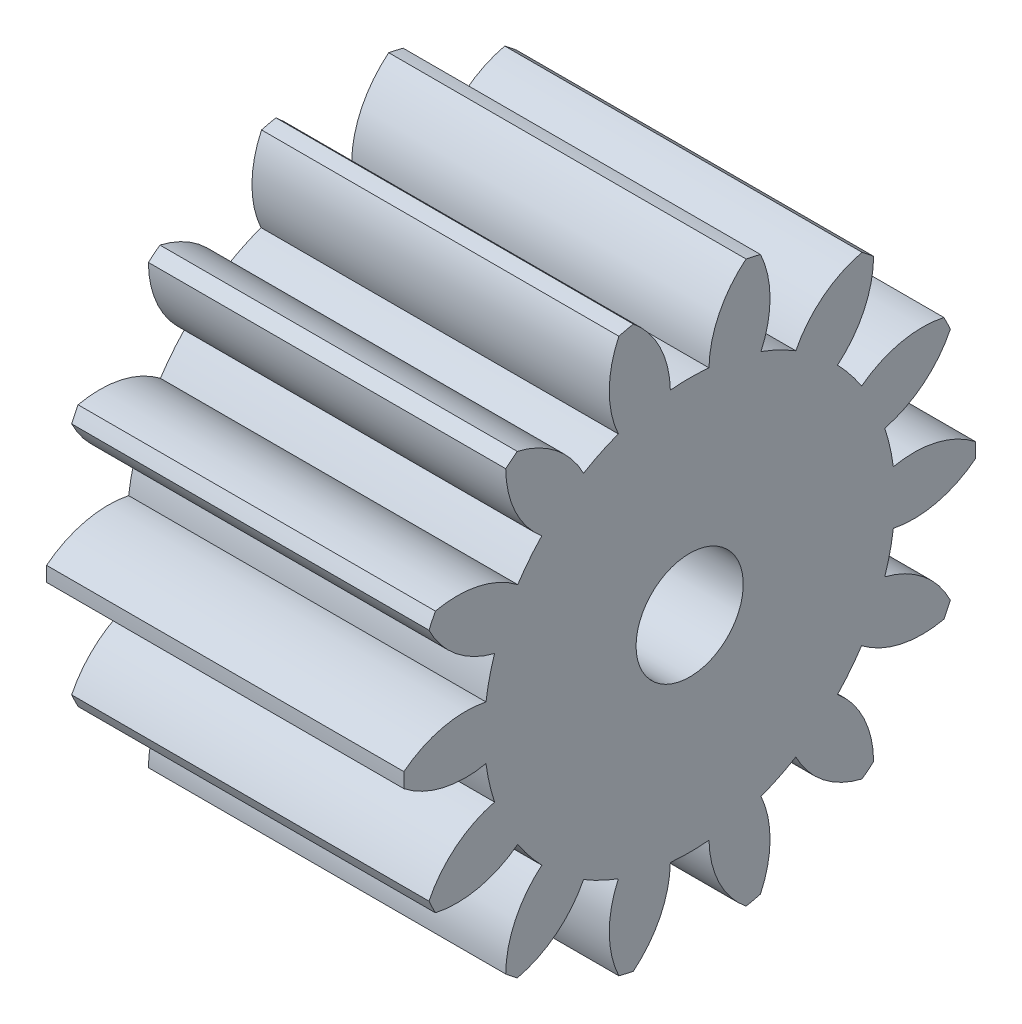
SolidWorks part; units mm, degrees
ref_plane "Plane1" through (0, 0, 0) normal (0, 0, 1) x (1, 0, 0)
ref_plane "Plane2" through (0, 0, 0) normal (0, 1, 0) x (1, 0, 0)
ref_plane "Plane3" through (0, 0, 0) normal (1, 0, 0) x (0, 0, -1)
other "Configuration Table"
sketch "HoldingSke" plane through (0, 0, 0) normal (0, 1, 0) x (1, 0, 0)
  line L0 (0, 0) -> (0.9703, -0.2419)
  line L1 (-15, 0) -> (100, 0) construction
  line L2 (0, 0) -> (-2.1039, 2.3779)
  line L3 (0, 0) -> (-11.863, 4.5341)
  line L4 (0, 0) -> (8.3795, 2.0892)
  line L5 (0, 0) -> (-46.8476, -17.4728)
  line L6 (0, 0) -> (-8.2896, -5.593)
  line L7 (-2.1039, 2.3779) -> (8.6586, 51.2059)
  line L8 (-76.2, 54.61) -> (-75.7, 54.61)
  line L9 (-71.009, 38.7566) -> (-53.1078, 45.2721)
  line L10 (-76.2, 71.12) -> (104.1128, 71.12)
  line L11 (0, 0) -> (-10, 0)
  line L12 (-76.2, 101.6) -> (-76.162, 101.6)
  line L13 (24.9733, 27.94) -> (52.9518, 28.4284)
  line L14 (24.9733, 27.94) -> (24.9743, 27.94)
  line L15 (24.9733, 27.94) -> (100.4006, 29.5858)
  line L16 (-63.627, -1) -> (-12.827, -1)
  circle A0 centre (0, 0) radius 1.5
  circle A1 centre (0, 0) radius 5.749
  circle A2 centre (0, 0) radius 37.5
  circle A3 centre (0, 0) radius 1.5
  dimension "MHD" = 11.498
  dimension "Hub_dia" = 75
  dimension "Bore" = 3
  dimension "MBD" = 3
  dimension "Num_teeth" = 14
  dimension "Pitch" = 1
  dimension "Overall_len" = 50
  dimension "Show_teeth" = 14
  dimension "Thickness" = 10
  dimension "OAL" = 50.0001
  dimension "T_dim" = 0.5
  dimension "Ap" = 20
  dimension "H" = 19.05
  dimension "Pitch_radius" = 180.3128
  dimension "Width" = 10
  dimension "Backlash" = 0.038
  dimension "Addendum_fac" = 1
  dimension "Dedendum_fac" = 1.25
  dimension "Clearance_fac" = 0.25
  dimension "Dedendum_add" = 0.001
  dimension "Module" = 1
sketch "BasProSke" plane through (0, 0, 0) normal (0, 1, 0) x (1, 0, 0)
  line L0 (-10, 0) -> (60, 0) construction
  line L1 (0, 0) -> (0, 8)
  line L2 (0, 0) -> (10, 0)
  line L3 (10, 0) -> (10, 8)
  line L4 (10, 8) -> (0, 8)
  dimension "Thickness" = 10
  dimension "Diameter" = 16
revolve "Base-Revolve" add sketch "BasProSke" angle 360 about L0
sketch "TooCutSke" plane through (0, 0, 0) normal (1, 0, 0) x (0, 0, -1)
  line L1 (0, 0) -> (0, 107) construction
  line L2 (0, 0) -> (-0.8502, 6.9482) construction
  line L3 (0, 0) -> (-3.0989, 13.5772) construction
  line L4 (-0.8502, 6.9482) -> (-1.5494, 6.7886) construction
  arc A0 (0.5404, 5.7235) -> (-0.5404, 5.7235) centre (0, 0) ccw
  arc A1 (1.6036, 7.8636) -> (-1.6036, 7.8636) centre (0, 0) ccw
  circle A2 centre (0, 0) radius 7 construction
  circle A3 centre (0, 0) radius 6.5778 construction
  arc A4 (-0.5404, 5.7235) -> (-1.6036, 7.8636) centre (-3.3398, 5.6669) ccw
  arc A5 (1.6036, 7.8636) -> (0.5404, 5.7235) centre (3.3398, 5.6669) ccw
  dimension "Root_dia" = 11.498
  dimension "Overcut_dia" = 16.0508
  dimension "Pitch_dia" = 14
  dimension "Base_dia" = 13.1557
  dimension "Flank_rad" = 2.8
  dimension "Half_ang" = 12.857
  dimension "Half_CT" = 0.7173
extrude "ToothCut" cut sketch "TooCutSke" along normal through all
fillet "Breaks" [suppressed] radius 0.02
fillet "RootFillets" [suppressed] radius 0.251
pattern_circular "TeethCuts" count 14 every 25.714 about axis through (-10, 0, 0) along (1, 0, 0) of "ToothCut", "RootFillets", "Breaks"
sketch "HubNeaOneSke" plane through (0, 0, 0) normal (-1, 0, 0) x (0, 0, 1)
  circle A0 centre (0, 0) radius 5.749
  dimension "Diameter" = 11.498
extrude "HubNearOne" [suppressed] add sketch "HubNeaOneSke" along normal blind 40.0001
sketch "HubNeaBotSke" plane through (0, 0, 0) normal (-1, 0, 0) x (0, 0, 1)
  circle A0 centre (0, 0) radius 5.749
  dimension "Diameter" = 11.498
extrude "HubNearBoth" [suppressed] add sketch "HubNeaBotSke" along normal blind 20
ref_plane "FarPln" through (10, 0, 0) normal (1, 0, 0) x (0, 0, -1)
sketch "HubFarSke" plane through (10, 0, 0) normal (1, 0, 0) x (0, 0, -1)
  circle A0 centre (0, 0) radius 5.749
  dimension "Diameter" = 11.498
extrude "HubFar" [suppressed] add sketch "HubFarSke" along normal blind 20
sketch "BorSke" plane through (0, 0, 0) normal (1, 0, 0) x (0, 0, -1)
  circle A0 centre (0, 0) radius 1.5
  dimension "Diameter" = 3
extrude "Bore" cut sketch "BorSke" along normal mid plane 100.0001
sketch "KeySke" plane through (0, 0, 0) normal (1, 0, 0) x (0, 0, -1)
  line L0 (-0.6, 0) -> (-0.6, 2)
  line L1 (-0.6, 2) -> (0.6, 2)
  line L2 (0.6, 2) -> (0.6, 0)
  line L3 (0, 0) -> (0, 34) construction
  line L4 (-0.6, 0) -> (0.6, 0)
  dimension "Offset" = 2
  dimension "Width" = 1.2
extrude "Keyway" [suppressed] cut sketch "KeySke" along normal mid plane 100.0001
pattern_circular "Keyway2" [suppressed] count 2 every 90 about axis through (-10, 0, 0) along (1, 0, 0)
sketch "Sketch1" plane through (0, 0, 0) normal (-1, 0, 0) x (0, 0, 1)
  line L0 (0, 0) -> (0, 3) construction
  line L1 (0, 2.7) -> (-0.38, 2.9758)
  line L2 (0, 2.7) -> (0.38, 2.9758)
  line L3 (0.6715, 2.6152) -> (1.1081, 2.7878)
  line L4 (0.6715, 2.6152) -> (0.372, 2.9768)
  line L5 (1.3007, 2.366) -> (1.7666, 2.4247)
  line L6 (1.3007, 2.366) -> (1.1006, 2.7908)
  line L7 (1.8483, 1.9682) -> (2.3141, 1.9092)
  line L8 (1.8483, 1.9682) -> (1.7601, 2.4294)
  line L9 (2.2797, 1.4467) -> (2.7162, 1.2737)
  line L10 (2.2797, 1.4467) -> (2.309, 1.9154)
  line L11 (2.5679, 0.8343) -> (2.9476, 0.5582)
  line L12 (2.5679, 0.8343) -> (2.7128, 1.281)
  line L13 (2.6947, 0.1695) -> (2.9938, -0.1924)
  line L14 (2.6947, 0.1695) -> (2.9461, 0.5661)
  line L15 (2.6522, -0.5059) -> (2.8519, -0.9309)
  line L16 (2.6522, -0.5059) -> (2.9943, -0.1843)
  line L17 (2.443, -1.1496) -> (2.5308, -1.6109)
  line L18 (2.443, -1.1496) -> (2.8544, -0.9232)
  line L19 (2.0804, -1.721) -> (2.0507, -2.1897)
  line L20 (2.0804, -1.721) -> (2.5351, -1.6041)
  line L21 (1.587, -2.1843) -> (1.4417, -2.6309)
  line L22 (1.587, -2.1843) -> (2.0566, -2.1841)
  line L23 (0.9939, -2.5104) -> (0.7422, -2.9067)
  line L24 (0.9939, -2.5104) -> (1.4488, -2.627)
  line L25 (0.3384, -2.6787) -> (-0.004, -3)
  line L26 (0.3384, -2.6787) -> (0.75, -2.9047)
  line L27 (-0.3384, -2.6787) -> (-0.75, -2.9047)
  line L28 (-0.3384, -2.6787) -> (0.004, -3)
  line L29 (-0.9939, -2.5104) -> (-1.4488, -2.627)
  line L30 (-0.9939, -2.5104) -> (-0.7422, -2.9067)
  line L31 (-1.587, -2.1843) -> (-2.0566, -2.1841)
  line L32 (-1.587, -2.1843) -> (-1.4417, -2.6309)
  line L33 (-2.0804, -1.721) -> (-2.5351, -1.6041)
  line L34 (-2.0804, -1.721) -> (-2.0507, -2.1897)
  line L35 (-2.443, -1.1496) -> (-2.8544, -0.9232)
  line L36 (-2.443, -1.1496) -> (-2.5308, -1.6109)
  line L37 (-2.6522, -0.5059) -> (-2.9943, -0.1843)
  line L38 (-2.6522, -0.5059) -> (-2.8519, -0.9309)
  line L39 (-2.6947, 0.1695) -> (-2.9461, 0.5661)
  line L40 (-2.6947, 0.1695) -> (-2.9938, -0.1924)
  line L41 (-2.5679, 0.8343) -> (-2.7128, 1.281)
  line L42 (-2.5679, 0.8343) -> (-2.9476, 0.5582)
  line L43 (-2.2797, 1.4467) -> (-2.309, 1.9154)
  line L44 (-2.2797, 1.4467) -> (-2.7162, 1.2737)
  line L45 (-1.8483, 1.9682) -> (-1.7601, 2.4294)
  line L46 (-1.8483, 1.9682) -> (-2.3141, 1.9092)
  line L47 (-1.3007, 2.366) -> (-1.1006, 2.7908)
  line L48 (-1.3007, 2.366) -> (-1.7666, 2.4247)
  line L49 (-0.6715, 2.6152) -> (-0.372, 2.9768)
  line L50 (-0.6715, 2.6152) -> (-1.1081, 2.7878)
  circle A0 centre (0, 0) radius 3
  circle A1 centre (0, 0) radius 2.7 construction
  point P8 (0, 0)
  point P9 (0, 0)
  point P83 (0, 0)
  dimension "D1" = 6
  dimension "D2" = 5.4
  dimension "D3" = 0.38
  dimension "D4" = 25
extrude "Cut-Extrude1" cut sketch "Sketch1" against normal blind 4 contours L49 L50 L47 L48 L45 L46 L43 L44 L41 L42 L39 L40 L37 L38 L35 L36 L33 L34 L31 L32 L29 L30 L27 L28 L25 L26 L23 L24 L21 L22 L19 L20 L17 L18 L15 L16 L13 L14 L11 L12 L9 L10 L7 L8 L5 L6 L3 L4 L2 L1
equation "' \"Module@HoldingSke\" = 6.35"
equation "' \"Num_teeth@HoldingSke\" = 12"
equation "' \"Ap@HoldingSke\" =  20"
equation "' \"Ap@HoldingSke\" = 20"
equation "' \"Width@HoldingSke\" = 0.5 * 25.4"
equation "' \"Hub_dia@HoldingSke\"= 1 * 25.4"
equation "' \"Hub_dia@HoldingSke\" = 1 * 25.4"
equation "' \"Overall_len@HoldingSke\" = 1.0 * 25.4"
equation "' \"Bore@HoldingSke\" = 0.75 * 25.4"
equation "' \"T_dim@HoldingSke\" = 0.1 * 25.4"
equation "' \"Width@KeySke\" = 0.25 * 25.4"
equation "' \"Show_teeth@HoldingSke\" = 13"
equation "' \"Backlash@HoldingSke\" = 0.009 * 25.4"
equation "' \"Addendum_fac@HoldingSke\" = 1.0"
equation "' \"Dedendum_fac@HoldingSke\" = 1.25"
equation "' \"Dedendum_add@HoldingSke\" = 0.00005 * 25.4"
equation "' \"Clearance_fac@HoldingSke\" = 0.25"
equation "\"Pitch@HoldingSke\" = 1 / \"Module@HoldingSke\""
equation "\"Overcut_dia@TooCutSke\" = (\"Num_teeth@HoldingSke\" + 2 * \"Addendum_fac@HoldingSke\") / \"Pitch@HoldingSke\" + 0.002 * 25.4"
equation "\"Pitch_dia@TooCutSke\" = \"Num_teeth@HoldingSke\" / \"Pitch@HoldingSke\""
equation "\"Base_dia@TooCutSke\" = \"Num_teeth@HoldingSke\" / \"Pitch@HoldingSke\" * cos((\"Ap@HoldingSke\"  * 3.14159265 / 180))"
equation "\"Root_dia@TooCutSke\" = (\"Num_teeth@HoldingSke\" + 2) / \"Pitch@HoldingSke\" - 2 * (\"Addendum_fac@HoldingSke\" + \"Dedendum_fac@HoldingSke\") / \"Pitch@HoldingSke\" - \"Dedendum_add@HoldingSke\" * 2"
equation "\"Half_ang@TooCutSke\" = 180 / \"Num_teeth@HoldingSke\""
equation "\"Half_CT@TooCutSke\" = \"Num_teeth@HoldingSke\" / \"Pitch@HoldingSke\" * sin((3.14159265 / 2 / \"Num_teeth@HoldingSke\")) / 2 - 7 * \"Backlash@HoldingSke\" / 4"
equation "\"Flank_rad@TooCutSke\" = \"Num_teeth@HoldingSke\" / \"Pitch@HoldingSke\" / 5"
equation "\"Radius@RootFillets\" = \"Clearance_fac@HoldingSke\" / \"Pitch@HoldingSke\" + \"Dedendum_add@HoldingSke\""
equation "\"Break_rad@Breaks\" = 0.02 / \"Pitch@HoldingSke\""
equation "\"Thickness@HoldingSke\" = \"Width@HoldingSke\""
equation "\"OAL@HoldingSke\" = \"Thickness@HoldingSke\""
equation "\"MHD@HoldingSke\" = (\"Num_teeth@HoldingSke\" + 2) / \"Pitch@HoldingSke\" - 2 * (\"Addendum_fac@HoldingSke\" + \"Dedendum_fac@HoldingSke\")  / \"Pitch@HoldingSke\" - \"Dedendum_add@HoldingSke\" * 2"
equation "\"MBD@HoldingSke\" = (\"Num_teeth@HoldingSke\" + 2) / \"Pitch@HoldingSke\" - 2 * (\"Addendum_fac@HoldingSke\" + \"Dedendum_fac@HoldingSke\")  / \"Pitch@HoldingSke\" - \"Dedendum_add@HoldingSke\" * 2 - 0.002 * 25.4"
equation "\"MHD@HoldingSke\" = ((sgn( \"MHD@HoldingSke\" - \"Hub_dia@HoldingSke\" )-1)*( \"MHD@HoldingSke\" - \"Hub_dia@HoldingSke\" ))/-2+ \"Hub_dia@HoldingSke\""
equation "\"MBD@HoldingSke\" = ((sgn( \"MBD@HoldingSke\" - \"Bore@HoldingSke\" )-1)*( \"MBD@HoldingSke\" - \"Bore@HoldingSke\" ))/-2+ \"Bore@HoldingSke\""
equation "\"OAL@HoldingSke\" = ((sgn( \"OAL@HoldingSke\" - \"Overall_len@HoldingSke\" )+1)*( \"OAL@HoldingSke\" - \"Overall_len@HoldingSke\" ))/2 + \"Overall_len@HoldingSke\" + 0.000002 * 25.4"
equation "\"Num_teeth@TeethCuts\" = int( \"Show_teeth@HoldingSke\" ) + 1"
equation "\"Num_teeth@TeethCuts\" = ((sgn( \"Num_teeth@TeethCuts\" - \"Num_teeth@HoldingSke\" )-1)*( \"Num_teeth@TeethCuts\" - \"Num_teeth@HoldingSke\" ))/-2+ \"Num_teeth@HoldingSke\""
equation "\"Num_teeth@TeethCuts\" = ((sgn( \"Num_teeth@TeethCuts\" - 2.0)+1)*( \"Num_teeth@TeethCuts\" - 2.0))/2 +2.0"
equation "\"Angle@TeethCuts\" = 360.0 / \"Num_teeth@HoldingSke\""
equation "\"Diameter@BasProSke\" = (\"Num_teeth@HoldingSke\" + 2 * \"Addendum_fac@HoldingSke\") / \"Pitch@HoldingSke\""
equation "\"Thickness@BasProSke\"  = \"Thickness@HoldingSke\""
equation "' \"Fillet_rad@BasProSke\" =  \"Thickness@HoldingSke\" * 0.05"
equation "' \"Fillet_rad@BasProSke\" = \"Thickness@HoldingSke\" * 0.05"
equation "\"MHD@HoldingSke\" = ((sgn( \"MHD@HoldingSke\" - \"Root_dia@TooCutSke\" )-1)*( \"MHD@HoldingSke\" - \"Root_dia@TooCutSke\" ))/-2+ \"Root_dia@TooCutSke\""
equation "\"Diameter@HubNeaOneSke\" = \"MHD@HoldingSke\""
equation "\"Length@HubNearOne\" = \"OAL@HoldingSke\" - \"Thickness@BasProSke\""
equation "\"Diameter@HubNeaBotSke\" = \"MHD@HoldingSke\""
equation "\"Length@HubNearBoth\" = ( \"OAL@HoldingSke\" - \"Thickness@BasProSke\" ) / 2.0"
equation "\"Thickness@FarPln\" = \"Thickness@BasProSke\""
equation "\"Diameter@HubFarSke\" = \"MHD@HoldingSke\""
equation "\"Length@HubFar\" = ( \"OAL@HoldingSke\" - \"Thickness@BasProSke\" ) / 2.0"
equation "\"Diameter@BorSke\" = \"MBD@HoldingSke\""
equation "\"D1@Bore\" = \"OAL@HoldingSke\" * 2.0"
equation "\"D1@Keyway\" = \"OAL@HoldingSke\" * 2.0"
equation "\"Offset@KeySke\" = \"T_dim@HoldingSke\" + \"MBD@HoldingSke\" / 2.0"
